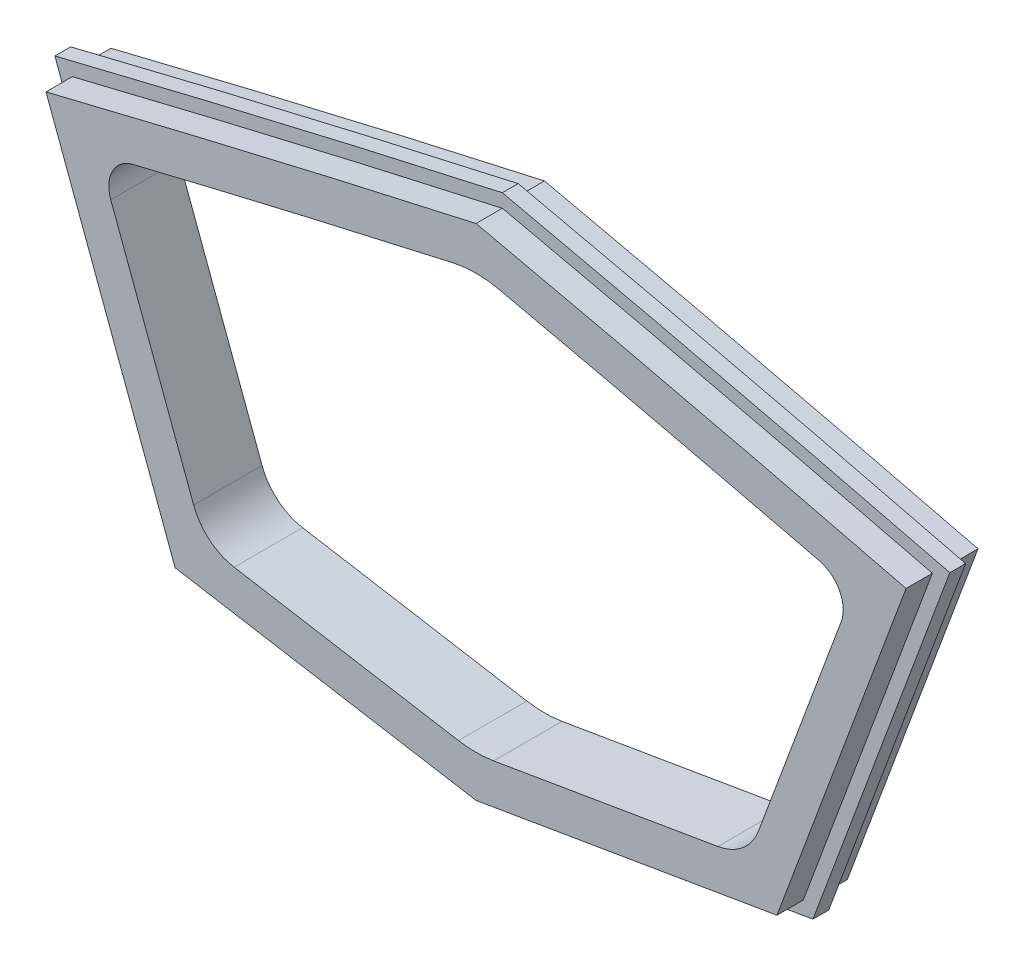
SolidWorks part; units mm, degrees
material "ABS"
ref_plane "Front Plane" through (0, 0, 0) normal (0, 0, 1) x (1, 0, 0)
ref_plane "Top Plane" through (0, 0, 0) normal (0, 1, 0) x (1, 0, 0)
ref_plane "Right Plane" through (0, 0, 0) normal (1, 0, 0) x (0, 0, -1)
sketch "Sketch1" plane through (0, 0, 0) normal (0, 0, 1) x (1, 0, 0)
  line L0 (51.6321, -61.1055) -> (71.7233, -7.0229)
  line L1 (-71.7233, -7.0229) -> (-51.6321, -61.1055)
  line L2 (-51.6321, -61.1055) -> (0, -69.8574)
  line L3 (0, -69.8574) -> (51.6321, -61.1055)
  line L8 (58.9956, -70) -> (85, 0.0001)
  line L9 (0, -80) -> (58.9956, -70)
  line L10 (-58.9956, -70) -> (0, -80)
  line L11 (-85, 0.0001) -> (-58.9956, -70)
  spline S0 degree 1 poles (71.7233, -7.0229) (0, 9.7572) knots 0 0 1 1 construction
  spline S1 degree 1 poles (0, 9.7572) (-71.7233, -7.0229) knots 0 0 1 1 construction
  spline S4 degree 3 poles (0, 19.9999) (-28.4207, 13.7115) (-56.7505, 7.0175) (-85, 0.0001) knots 0 0 0 0 1 1 1 1
  spline S5 degree 3 poles (85, 0.0001) (56.7505, 7.0175) (28.4208, 13.7115) (0, 19.9999) knots 0 0 0 0 1 1 1 1
  spline S6 degree 3 poles (71.7233, -7.0229) (65.7602, -5.5606) (53.8262, -2.6655) (35.9064, 1.5822) (17.9654, 5.7307) (5.9913, 8.427) (0, 9.7572) knots 0.128509 0.128509 0.128509 0.128509 0.340026 0.551543 0.76306 0.974577 0.974577 0.974577 0.974577
  spline S7 degree 3 poles (0, 9.7572) (-5.9913, 8.427) (-17.9654, 5.7308) (-35.9064, 1.5822) (-53.8262, -2.6654) (-65.7603, -5.5605) (-71.7233, -7.0229) knots 0.025423 0.025423 0.025423 0.025423 0.23694 0.448457 0.659974 0.871491 0.871491 0.871491 0.871491
  dimension "D2" = 10
extrude "Boss-Extrude1" add sketch "Sketch1" along normal blind 3
fillet "Fillet1" radius 20 2 edges at (0, -69.8574, 1.5) (0, 9.7572, 1.5)
fillet "Fillet2" radius 10 2 edges at (51.6321, -61.1055, 1.5) (-51.6321, -61.1055, 1.5)
fillet "Fillet3" radius 6 2 edges at (71.7233, -7.0229, 1.5) (-71.7233, -7.0229, 1.5)
sketch "Sketch2" plane through (0, 0, 3) normal (0, 0, 1) x (1, 0, 0)
  line L4 (-69.376, -13.3415) -> (-53.6427, -55.6934) construction
  line L5 (-45.9398, -62.0704) -> (-3.3424, -69.2908) construction
  line L6 (3.3424, -69.2908) -> (45.9398, -62.0704) construction
  line L7 (53.6427, -55.6934) -> (69.376, -13.3416) construction
  line L8 (-81.682, -1.7527) -> (-57.1548, -67.7764)
  line L9 (-57.1548, -67.7764) -> (0, -77.4643)
  line L10 (0, -77.4643) -> (57.1548, -67.7764)
  line L11 (57.1548, -67.7764) -> (81.6819, -1.7527)
  line L12 (-81.682, -1.7527) -> (-57.1548, -67.7764)
  line L13 (-57.1548, -67.7764) -> (0, -77.4643)
  line L14 (0, -77.4643) -> (57.1548, -67.7764)
  line L15 (57.1548, -67.7764) -> (81.6819, -1.7527)
  line L16 (-69.376, -13.3415) -> (-53.6427, -55.6934)
  line L17 (-45.9398, -62.0704) -> (-3.3424, -69.2908)
  line L18 (3.3424, -69.2908) -> (45.9398, -62.0704)
  line L19 (53.6427, -55.6934) -> (69.376, -13.3416)
  arc A1 (-65.1699, -5.4221) -> (-69.376, -13.3415) centre (-63.7516, -11.2521) ccw construction
  arc A2 (-53.6427, -55.6934) -> (-45.9398, -62.0704) centre (-44.2686, -52.211) ccw construction
  arc A3 (-3.3424, -69.2908) -> (3.3424, -69.2908) centre (0, -49.5721) ccw construction
  arc A4 (45.9398, -62.0704) -> (53.6427, -55.6934) centre (44.2686, -52.211) ccw construction
  arc A5 (69.376, -13.3416) -> (65.1699, -5.4222) centre (63.7515, -11.2521) ccw construction
  arc A6 (4.3632, 8.7852) -> (-4.3632, 8.7852) centre (0, -10.7331) ccw construction
  arc A7 (-65.1699, -5.4221) -> (-69.376, -13.3415) centre (-63.7516, -11.2521) ccw
  arc A8 (-53.6427, -55.6934) -> (-45.9398, -62.0704) centre (-44.2686, -52.211) ccw
  arc A9 (-3.3424, -69.2908) -> (3.3424, -69.2908) centre (0, -49.5721) ccw
  arc A10 (45.9398, -62.0704) -> (53.6427, -55.6934) centre (44.2686, -52.211) ccw
  arc A11 (69.376, -13.3416) -> (65.1699, -5.4222) centre (63.7515, -11.2521) ccw
  arc A12 (4.3632, 8.7852) -> (-4.3632, 8.7852) centre (0, -10.7331) ccw
  spline S3 degree 3 poles (2856.2231, -710.7914) (1223.1942, 104.564) (579.2853, 143.8341) (-35.9064, 1.5822) (-1030.2564, -234.1159) (-1933.2229, -901.7007) (1099.9889, 2490.3845) knots -21.098589 -21.098589 -21.098589 -21.098589 0.23694 0.448457 0.659974 35.447452 35.447452 35.447452 35.447452 only from (-4.3632, 8.7852) to (-65.1699, -5.4221) construction
  spline S4 degree 3 poles (3213.9817, 1579.7272) (901.2899, -2961.498) (-164.1911, 3027.1999) (-2889.2123, -2307.1163) knots -36.346529 -36.346529 -36.346529 -36.346529 30.527536 30.527536 30.527536 30.527536 only from (81.6819, -1.7527) to (0, 17.4394)
  spline S5 degree 3 poles (2884.6712, -2310.9837) (170.5811, 3032.8885) (-910.5565, -2969.0724) (-3206.0132, 1587.7256) knots -29.53804 -29.53804 -29.53804 -29.53804 37.373414 37.373414 37.373414 37.373414 only from (0, 17.4394) to (-81.682, -1.7527)
  spline S6 degree 3 poles (81.6819, -1.7527) (54.5322, 4.9703) (27.3082, 11.392) (0, 17.4394) knots 0 0 0 0 1 1 1 1
  spline S7 degree 3 poles (0, 17.4394) (-27.3081, 11.392) (-54.5323, 4.9703) (-81.682, -1.7527) knots 0 0 0 0 1 1 1 1
  spline S8 degree 3 poles (-1113.3341, 2488.3803) (1932.0695, -900.8143) (1029.5812, -233.957) (35.9064, 1.5822) (-580.0364, 144.0085) (-1224.8367, 104.4791) (-2854.4298, -715.5725) knots -34.423595 -34.423595 -34.423595 -34.423595 0.340026 0.551543 0.76306 22.125182 22.125182 22.125182 22.125182 only from (65.1699, -5.4222) to (4.3632, 8.7852) construction
  spline S9 degree 3 poles (-4.3632, 8.7852) (-8.8983, 7.7714) (-19.4173, 5.395) (-35.9064, 1.5822) (-51.6385, -2.1469) (-61.389, -4.5023) (-65.1699, -5.4221) knots 0.076777 0.076777 0.076777 0.076777 0.23694 0.448457 0.659974 0.794023 0.794023 0.794023 0.794023
  spline S10 degree 3 poles (65.1699, -5.4222) (61.389, -4.5024) (51.6385, -2.1469) (35.9064, 1.5822) (19.4173, 5.395) (8.8983, 7.7714) (4.3632, 8.7852) knots 0.205976 0.205976 0.205976 0.205976 0.340026 0.551543 0.76306 0.923223 0.923223 0.923223 0.923223
  dimension "D1" = 2.5
extrude "Boss-Extrude2" add sketch "Sketch2" along normal blind 5
sketch "Sketch3" plane through (0, 0, 0) normal (0, 0, -1) x (-1, 0, 0)
  line L0 (69.376, -13.3415) -> (53.6427, -55.6934) construction
  line L1 (45.9398, -62.0704) -> (3.3424, -69.2908) construction
  line L2 (-3.3424, -69.2908) -> (-45.9398, -62.0704) construction
  line L3 (-53.6427, -55.6934) -> (-69.376, -13.3416) construction
  line L12 (57.5229, -68.2211) -> (82.3456, -1.4019)
  line L13 (0, -77.9715) -> (57.5229, -68.2211)
  line L14 (-57.5229, -68.2211) -> (0, -77.9715)
  line L15 (-82.3456, -1.402) -> (-57.5229, -68.2211)
  line L16 (57.5229, -68.2211) -> (82.3456, -1.4019)
  line L17 (0, -77.9715) -> (57.5229, -68.2211)
  line L18 (-57.5229, -68.2211) -> (0, -77.9715)
  line L19 (-82.3456, -1.402) -> (-57.5229, -68.2211)
  line L20 (-53.6427, -55.6934) -> (-69.376, -13.3416)
  line L21 (-3.3424, -69.2908) -> (-45.9398, -62.0704)
  line L22 (45.9398, -62.0704) -> (3.3424, -69.2908)
  line L23 (69.376, -13.3415) -> (53.6427, -55.6934)
  arc A0 (4.3632, 8.7852) -> (-4.3632, 8.7852) centre (0, -10.7331) ccw construction
  arc A1 (69.376, -13.3415) -> (65.1699, -5.4221) centre (63.7516, -11.2521) ccw construction
  arc A2 (45.9398, -62.0704) -> (53.6427, -55.6934) centre (44.2686, -52.211) ccw construction
  arc A3 (-3.3424, -69.2908) -> (3.3424, -69.2908) centre (0, -49.5721) ccw construction
  arc A4 (-53.6427, -55.6934) -> (-45.9398, -62.0704) centre (-44.2686, -52.211) ccw construction
  arc A5 (-65.1699, -5.4222) -> (-69.376, -13.3416) centre (-63.7515, -11.2521) ccw construction
  arc A6 (-65.1699, -5.4222) -> (-69.376, -13.3416) centre (-63.7515, -11.2521) ccw
  arc A7 (-53.6427, -55.6934) -> (-45.9398, -62.0704) centre (-44.2686, -52.211) ccw
  arc A8 (-3.3424, -69.2908) -> (3.3424, -69.2908) centre (0, -49.5721) ccw
  arc A9 (45.9398, -62.0704) -> (53.6427, -55.6934) centre (44.2686, -52.211) ccw
  arc A10 (69.376, -13.3415) -> (65.1699, -5.4221) centre (63.7516, -11.2521) ccw
  arc A11 (4.3632, 8.7852) -> (-4.3632, 8.7852) centre (0, -10.7331) ccw
  spline S0 degree 3 poles (-1947.6207, -293.2287) (-956.0423, 113.109) (-452.1928, 114.4463) (35.9064, 1.5822) (950.4936, -215.2091) (1786.9263, -796.7733) (-436.8515, 1741.9638) knots -16.603487 -16.603487 -16.603487 -16.603487 0.23694 0.448457 0.659974 32.623003 32.623003 32.623003 32.623003 only from (4.3632, 8.7852) to (65.1699, -5.4221) construction
  spline S1 degree 3 poles (448.3337, 1741.5955) (-1786.0704, -796.1529) (-949.9918, -215.0912) (-35.9064, 1.5822) (452.7161, 114.5678) (957.1703, 113.1138) (1947.0313, -295.4162) knots -31.605284 -31.605284 -31.605284 -31.605284 0.340026 0.551543 0.76306 17.622017 17.622017 17.622017 17.622017 only from (-65.1699, -5.4222) to (-4.3632, 8.7852) construction
  spline S2 degree 3 poles (-65.1699, -5.4222) (-61.389, -4.5024) (-51.6385, -2.1469) (-35.9064, 1.5822) (-19.4173, 5.395) (-8.8983, 7.7714) (-4.3632, 8.7852) knots 0.205976 0.205976 0.205976 0.205976 0.340026 0.551543 0.76306 0.923223 0.923223 0.923223 0.923223
  spline S3 degree 3 poles (4.3632, 8.7852) (8.8983, 7.7714) (19.4173, 5.395) (35.9064, 1.5822) (51.6385, -2.1469) (61.389, -4.5023) (65.1699, -5.4221) knots 0.076777 0.076777 0.076777 0.076777 0.23694 0.448457 0.659974 0.794023 0.794023 0.794023 0.794023
  spline S6 degree 3 poles (4646.3207, -7000.7919) (-175.289, 8164.4712) (-746.1646, -8162.0124) (-4823.9445, 6347.4365) knots -45.774908 -45.774908 -45.774908 -45.774908 55.413459 55.413459 55.413459 55.413459 only from (0.0002, 17.9394) to (-82.3456, -1.402)
  spline S7 degree 3 poles (4788.9478, 6366.1218) (777.4372, -8178.3949) (149.9267, 8177.7508) (-4625.943, -7011.1019) knots -54.435451 -54.435451 -54.435451 -54.435451 46.785912 46.785912 46.785912 46.785912 only from (82.3456, -1.4019) to (0.0002, 17.9394)
  spline S8 degree 3 poles (0.0002, 17.9394) (-27.5313, 11.8519) (-54.9768, 5.379) (-82.3456, -1.402) knots -0.075105 -0.075105 -0.075105 -0.075105 1.011252 1.011252 1.011252 1.011252
  spline S9 degree 3 poles (82.3456, -1.4019) (54.977, 5.379) (27.5316, 11.8519) (0.0002, 17.9394) knots -0.011247 -0.011247 -0.011247 -0.011247 1.075105 1.075105 1.075105 1.075105
  dimension "D2" = 0
extrude "Boss-Extrude3" add sketch "Sketch3" along normal blind 5
